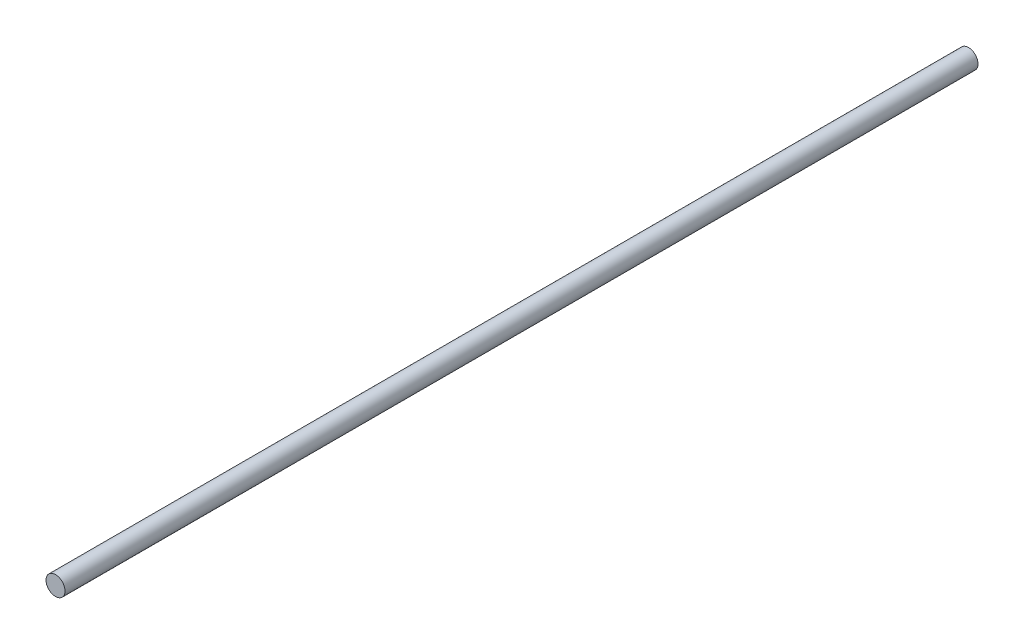
SolidWorks part; units mm, degrees
material "AISI 1020"
ref_plane "Front Plane" through (0, 0, 0) normal (0, 0, 1) x (1, 0, 0)
ref_plane "Top Plane" through (0, 0, 0) normal (0, 1, 0) x (1, 0, 0)
ref_plane "Right Plane" through (0, 0, 0) normal (1, 0, 0) x (0, 0, -1)
sketch "Sketch3" plane through (0, 0, 0) normal (0, 0, 1) x (1, 0, 0)
  circle A0 centre (0, 0) radius 3.175
  dimension "D1" = 6.35
extrude "Boss-Extrude1" add sketch "Sketch3" along normal blind 304.8
